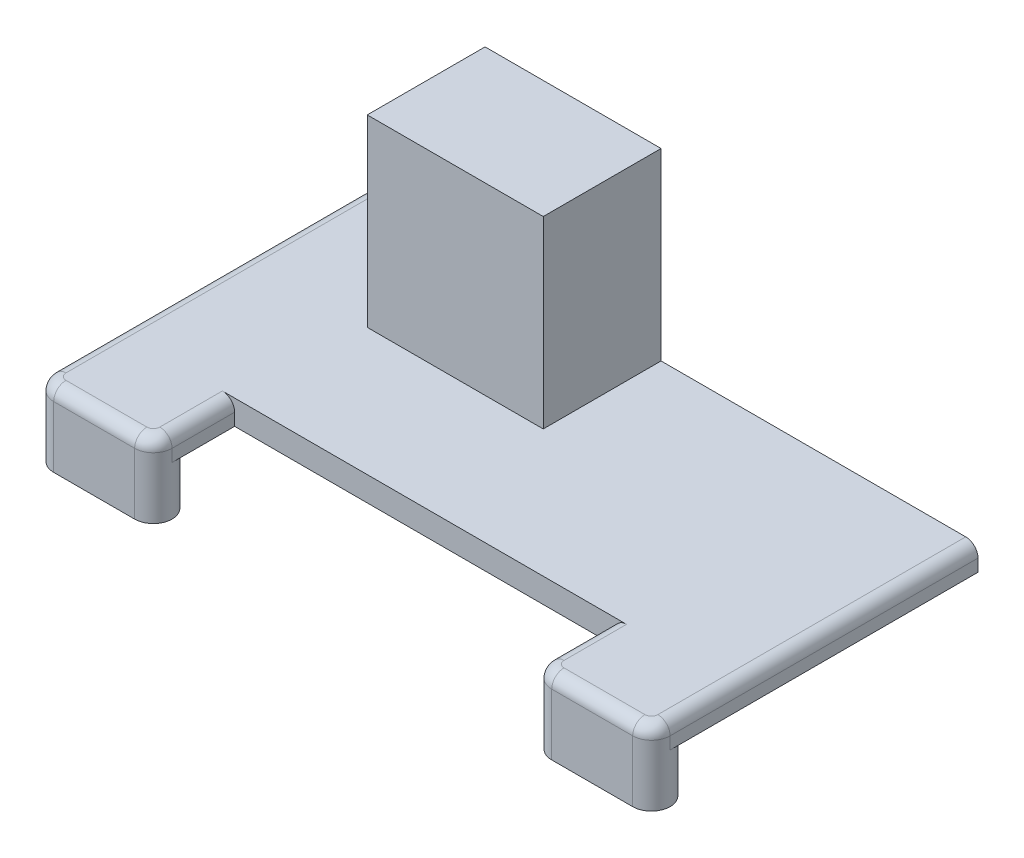
SolidWorks part; units mm, degrees
ref_plane "Front" through (0, 0, 0) normal (0, 0, 1) x (1, 0, 0)
ref_plane "Top" through (0, 0, 0) normal (0, 1, 0) x (1, 0, 0)
ref_plane "Right" through (0, 0, 0) normal (1, 0, 0) x (0, 0, -1)
sketch "Sketch1" plane through (0, 0, 0) normal (0, 1, 0) x (1, 0, 0)
  line L0 (0, -55) -> (0, 55) construction
  line L5 (-23.6, 10.5423) -> (-17, 10.5423)
  line L6 (-23.6, 7.4923) -> (-17, 7.4923)
  line L7 (23.6, 7.4923) -> (17, 7.4923)
  line L8 (23.6, 10.5423) -> (17, 10.5423)
  arc A0 (-23.6, 10.5423) -> (-23.6, 7.4923) centre (-23.6, 9.0173) ccw
  arc A1 (-17, 7.4923) -> (-17, 10.5423) centre (-17, 9.0173) ccw
  arc A2 (23.6, 10.5423) -> (23.6, 7.4923) centre (23.6, 9.0173) cw
  arc A3 (17, 7.4923) -> (17, 10.5423) centre (17, 9.0173) cw
  dimension "D1" = 3.05
  dimension "D2" = 6.6
  dimension "D3" = 17
extrude "Boss-Extrude1" add sketch "Sketch1" along normal blind 4
sketch "Sketch3" plane through (0, 4, 0) normal (0, 1, 0) x (1, 0, 0)
  line L1 (17, 7.4923) -> (23.6, 7.4923) construction
  line L2 (-23.6, 7.4923) -> (-17, 7.4923) construction
  line L5 (17, 7.4923) -> (23.6, 7.4923)
  line L6 (-23.6, 7.4923) -> (-17, 7.4923)
  line L8 (-25.125, 9.0173) -> (-25.125, 17.3059)
  line L9 (-15.475, 14.1173) -> (15.475, 14.1173)
  line L11 (-25.125, 34.1173) -> (25.125, 34.1173)
  line L13 (-15.475, 9.0173) -> (-15.475, 14.1173)
  line L14 (0, -55) -> (0, 55) construction
  line L15 (23.6, 7.4923) -> (17, 7.4923)
  line L16 (15.475, 9.0173) -> (15.475, 14.1173)
  line L17 (15.475, 14.1173) -> (-15.475, 14.1173)
  line L18 (-25.125, 17.3059) -> (-25.125, 34.1173)
  line L19 (25.125, 34.1173) -> (25.125, 17.3059)
  line L20 (25.125, 9.0173) -> (25.125, 17.3059)
  arc A0 (23.6, 7.4923) -> (23.6, 10.5423) centre (23.6, 9.0173) ccw construction
  arc A1 (17, 10.5423) -> (17, 7.4923) centre (17, 9.0173) ccw construction
  arc A2 (-23.6, 10.5423) -> (-23.6, 7.4923) centre (-23.6, 9.0173) ccw construction
  arc A3 (-17, 7.4923) -> (-17, 10.5423) centre (-17, 9.0173) ccw construction
  arc A4 (23.6, 7.4923) -> (25.125, 9.0173) centre (23.6, 9.0173) ccw
  arc A5 (15.475, 9.0173) -> (17, 7.4923) centre (17, 9.0173) ccw
  arc A6 (-25.125, 9.0173) -> (-23.6, 7.4923) centre (-23.6, 9.0173) ccw
  arc A7 (-17, 7.4923) -> (-15.475, 9.0173) centre (-17, 9.0173) ccw
  arc A8 (25.125, 9.0173) -> (23.6, 7.4923) centre (23.6, 9.0173) cw
  arc A9 (17, 7.4923) -> (15.475, 9.0173) centre (17, 9.0173) cw
  arc M5 (-23.6, 10.5423) -> (-23.6, 7.4923) centre (-23.6, 9.0173) ccw
  line M6 (-23.6, 7.4923) -> (-17, 7.4923)
  arc M7 (-17, 7.4923) -> (-17, 10.5423) centre (-17, 9.0173) ccw
  line M8 (-17, 10.5423) -> (-23.6, 10.5423)
  dimension "D1" = 5.1
  dimension "D2" = 20
extrude "Boss-Extrude3" add sketch "Sketch3" along normal blind 2 contours L16 A5 L5 A4 L20 L19 L11 L18 L8 L13 L9 M5 M8 M7 | M8 M5 M6 M7
fillet "Fillet2" radius 1 10 edges at (-25.125, 6, -21.5673) (-24.6783, 6, -7.9389) (-15.475, 6, -11.5673) (-15.9217, 6, -7.9389) (15.475, 6, -11.5673) (15.9217, 6, -7.9389) (25.125, 6, -21.5673) (24.6783, 6, -7.9389) (-20.3, 6, -7.4923) (20.3, 6, -7.4923)
sketch "Sketch4" plane through (0, 6, 0) normal (0, 1, 0) x (1, 0, 0)
  line L0 (-24.125, 34.1173) -> (24.125, 34.1173) construction
  line L1 (-15.0591, 34.1173) -> (-0.7115, 34.1173)
  line L2 (-15.0591, 34.1173) -> (-15.0591, 24.5127)
  line L3 (-15.0591, 24.5127) -> (-0.7115, 24.5127)
  line L4 (-0.7115, 34.1173) -> (-0.7115, 24.5127)
extrude "Boss-Extrude4" add sketch "Sketch4" along normal blind 15
